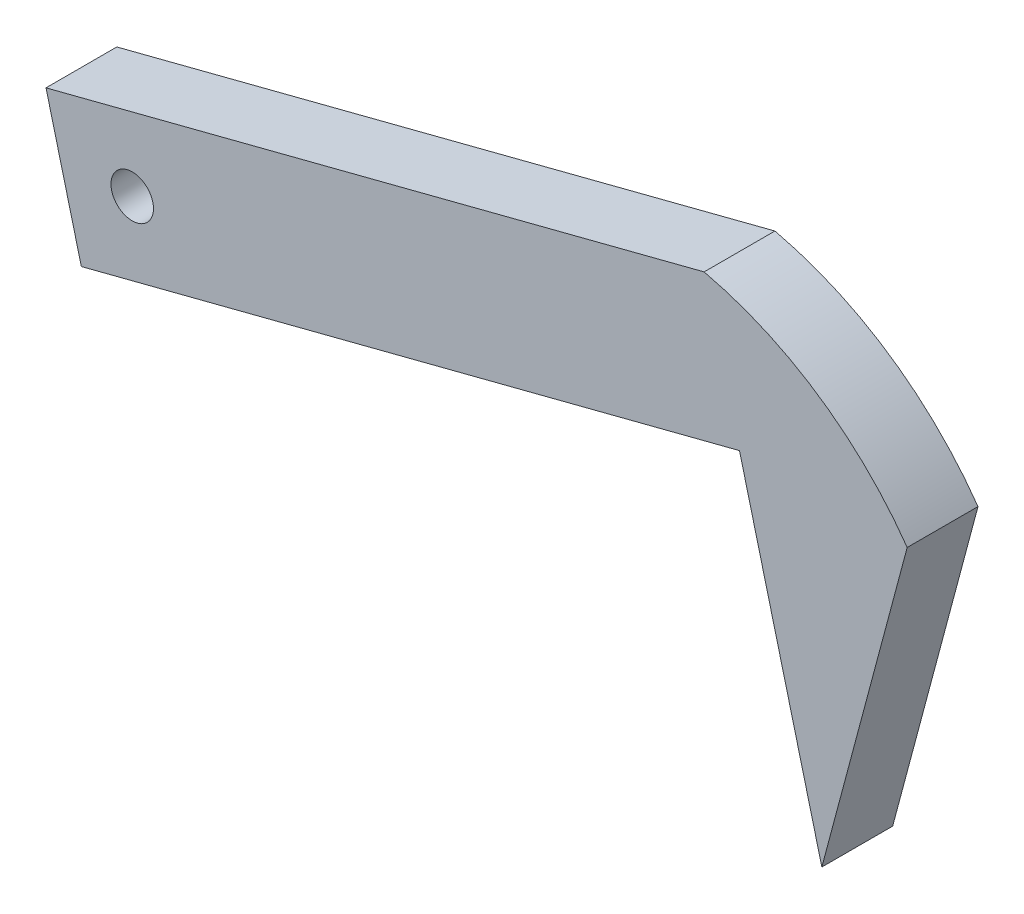
SolidWorks part; units mm, degrees
ref_plane "Plan de face" through (0, 0, 0) normal (0, 0, 1) x (1, 0, 0)
ref_plane "Plan de dessus" through (0, 0, 0) normal (0, 1, 0) x (1, 0, 0)
ref_plane "Plan de droite" through (0, 0, 0) normal (1, 0, 0) x (0, 0, -1)
sketch "Esquisse1" plane through (0, 0, 0) normal (0, 0, 1) x (1, 0, 0)
  line L1 (60.8217, 2.2986) -> (54.793, -20.2639)
  line L3 (48.9767, 2.2986) -> (2.4962, -9.6834)
  line L4 (2.4962, -9.6834) -> (0, 0)
  line L5 (0, 0) -> (46.4804, 11.982)
  line L6 (48.9767, 2.2986) -> (54.793, -20.2639)
  arc A0 (46.4804, 11.982) -> (60.8217, 2.2986) centre (40.9494, -11.6712) cw
  circle A1 centre (6.0898, -3.5936) radius 1.5
  point P18 (1.2481, -4.8417)
  dimension "D5" = 3
  dimension "D1" = 10
  dimension "D2" = 60
  dimension "D3" = 48
  dimension "D4" = 48
  dimension "D6" = 5
  dimension "D7" = 5
extrude "Boss.-Extru.1" add sketch "Esquisse1" along normal blind 5
